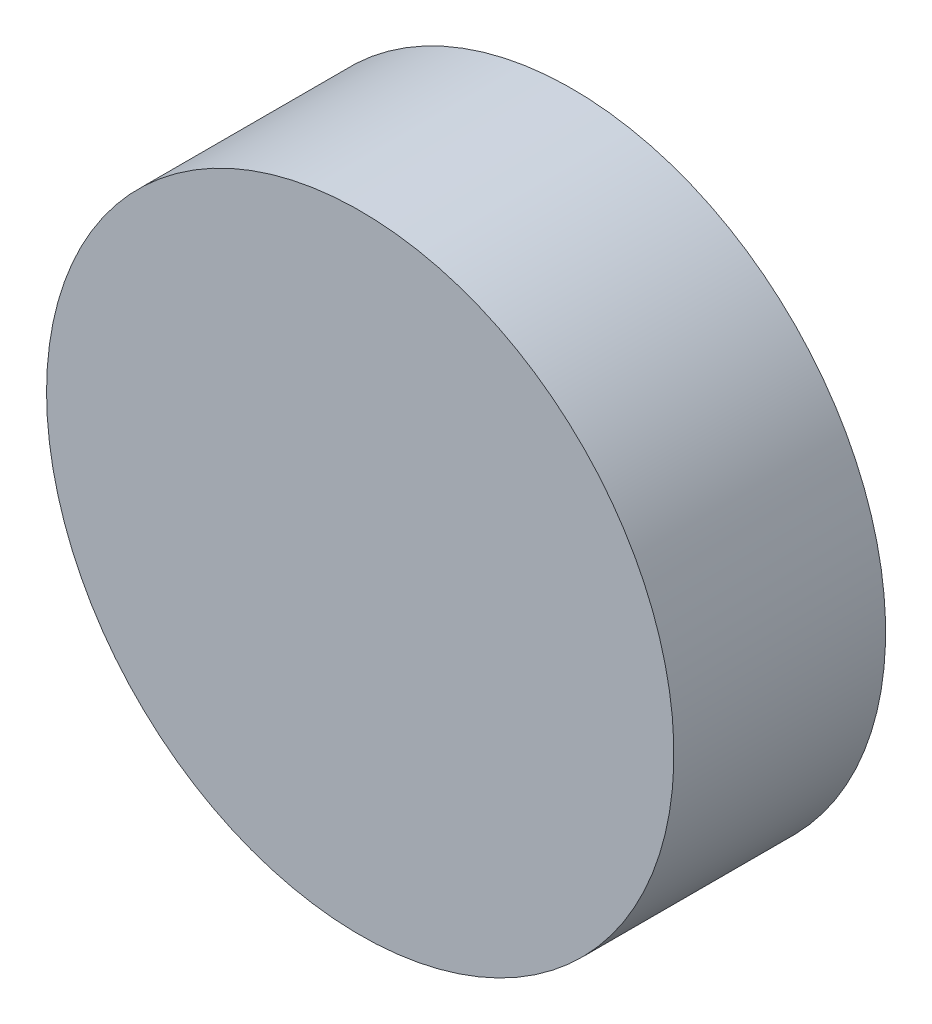
SolidWorks part; units mm, degrees
ref_plane "Alzado" through (0, 0, 0) normal (0, 0, 1) x (1, 0, 0)
ref_plane "Planta" through (0, 0, 0) normal (0, 1, 0) x (1, 0, 0)
ref_plane "Vista lateral" through (0, 0, 0) normal (1, 0, 0) x (0, 0, -1)
sketch "Croquis1" plane through (0, 0, 0) normal (0, 0, 1) x (1, 0, 0)
  circle A0 centre (0, 0) radius 2
  dimension "D1" = 4
extrude "Saliente-Extruir1" add sketch "Croquis1" along normal blind 1.35
